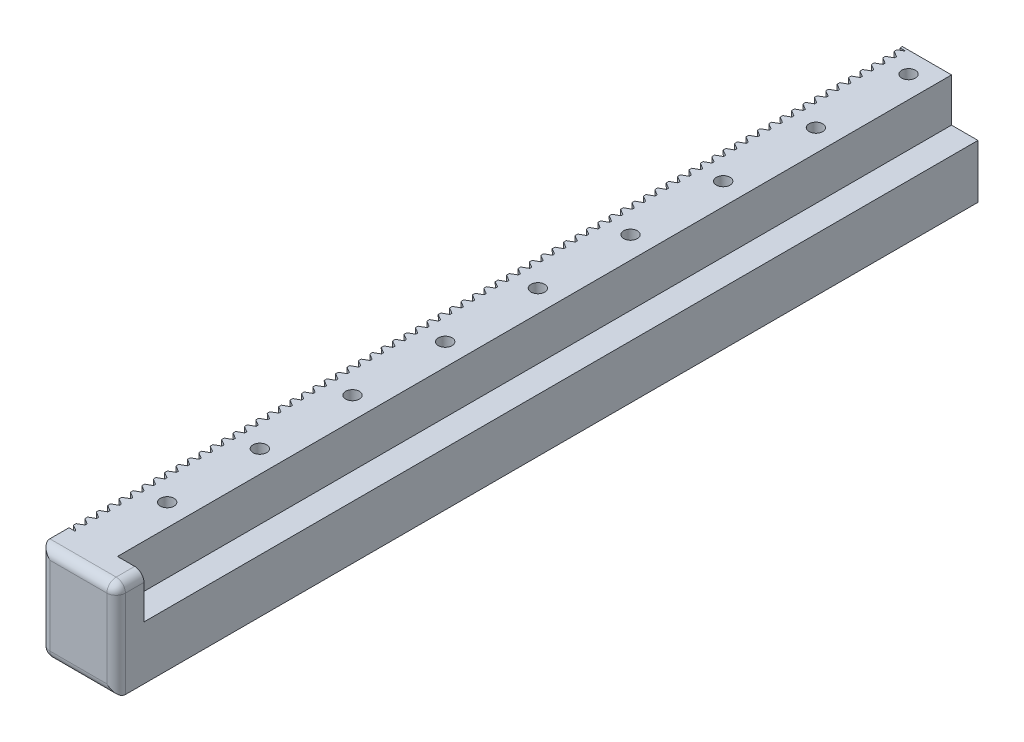
SolidWorks part; units mm, degrees
ref_plane "Front Plane" through (0, 0, 0) normal (0, 0, 1) x (1, 0, 0)
ref_plane "Top Plane" through (0, 0, 0) normal (0, 1, 0) x (1, 0, 0)
ref_plane "Right Plane" through (0, 0, 0) normal (1, 0, 0) x (0, 0, -1)
sketch "Sketch1" plane through (0, 0, 0) normal (0, 0, 1) x (1, 0, 0)
  line L0 (8.155, 3.5595) -> (8.155, -2.2289)
  line L1 (6.255, 0) -> (0.2882, 0)
  line L3 (0, 8.253) -> (5.3, 8.253)
  line L4 (5.3, 3.5595) -> (5.3, 8.253)
  line L5 (0.2882, 0) -> (0, 8.253)
  line L7 (5.3, 3.5595) -> (8.155, 3.5595)
  line L11 (8.155, -2.2289) -> (6.255, -2.2289)
  line L12 (6.255, 0) -> (6.255, -2.2289)
  dimension "D1" = 5.3
  dimension "D2" = 8.253
  dimension "D3" = 1.9
  dimension "D4" = 2.855
  dimension "D6" = 88
extrude "Boss-Extrude1" add sketch "Sketch1" along normal blind 90
sketch "Sketch2" plane through (0, 0, 90) normal (0, 0, 1) x (1, 0, 0)
  line L1 (0, 8.253) -> (8.155, 8.253)
  line L2 (0, 8.253) -> (0, -2.2289)
  line L3 (0, -2.2289) -> (8.155, -2.2289)
  line L4 (8.155, 8.253) -> (8.155, -2.2289)
extrude "Boss-Extrude2" add sketch "Sketch2" along normal blind 3
fillet "Fillet1" radius 1 6 edges at (4.0775, 8.253, 93) (8.155, 3.0121, 93) (4.0775, -2.2289, 93) (0, 3.0121, 93) (0, -2.2289, 91.5) (8.155, 8.253, 91.5)
sketch "Sketch3" plane through (5.3, 0, 0) normal (0, 1, 0) x (0, 0, -1)
  line L0 (-87.5812, 4.6774) -> (-88.0715, 5.5507)
  line L1 (-88.0715, 5.5507) -> (-88.5898, 4.6774)
  line L2 (-88.8112, 4.6774) -> (-89.3015, 5.5507)
  line L3 (-89.3015, 5.5507) -> (-89.8198, 4.6774)
  line L4 (-89.3983, 4.4813) -> (-88.7803, 4.4739) [skipped]
  line L5 (-86.3512, 4.6774) -> (-86.8415, 5.5507)
  line L6 (-86.8415, 5.5507) -> (-87.3598, 4.6774)
  line L7 (-85.1212, 4.6774) -> (-85.6115, 5.5507)
  line L8 (-85.6115, 5.5507) -> (-86.1298, 4.6774)
  line L149 (-89.9324, 4.6774) -> (-89.9324, 6.9221)
  line L150 (-89.9324, 6.9221) -> (-85.1212, 6.9221)
  line L154 (-89.8198, 4.6774) -> (-89.9324, 4.6774)
  line L155 (-88.5898, 4.6774) -> (-88.8112, 4.6774)
  line L156 (-87.3598, 4.6774) -> (-87.5812, 4.6774)
  line L157 (-86.1298, 4.6774) -> (-86.3512, 4.6774)
  line L158 (-85.1212, 6.9221) -> (-85.1212, 4.6774)
  line L160 (-83.1621, 7.6054) -> (-83.4775, 7.0739) [skipped]
  line L161 (-83.735, 6.5902) -> (-84.3402, 7.668) [skipped]
  line L162 (-81.9321, 7.6054) -> (-82.5629, 6.5424) [skipped]
  line L163 (-82.505, 6.5902) -> (-83.1102, 7.668) [skipped]
  line L164 (-80.7021, 7.6054) -> (-81.3329, 6.5424) [skipped]
  line L165 (-81.275, 6.5902) -> (-81.8802, 7.668) [skipped]
  line L166 (-79.4721, 7.6054) -> (-80.1029, 6.5424) [skipped]
  line L167 (-80.045, 6.5902) -> (-80.6502, 7.668) [skipped]
  line L168 (-78.2421, 7.6054) -> (-78.8729, 6.5424) [skipped]
  line L169 (-78.815, 6.5902) -> (-79.4202, 7.668) [skipped]
  line L170 (-77.0121, 7.6054) -> (-77.6429, 6.5424) [skipped]
  line L171 (-75.7821, 7.6054) -> (-76.4129, 6.5424) [skipped]
  line L172 (-84.965, 6.5902) -> (-85.5702, 7.668) [skipped]
  line L173 (-49.295, 6.5902) -> (-49.9002, 7.668) [skipped]
  line L174 (-47.4921, 7.6054) -> (-48.1229, 6.5424) [skipped]
  line L175 (-48.065, 6.5902) -> (-48.6702, 7.668) [skipped]
  line L176 (-46.2621, 7.6054) -> (-46.8929, 6.5424) [skipped]
  line L177 (-46.835, 6.5902) -> (-47.4402, 7.668) [skipped]
  line L178 (-45.0321, 7.6054) -> (-45.6629, 6.5424) [skipped]
  line L179 (-45.605, 6.5902) -> (-46.2102, 7.668) [skipped]
  line L180 (-43.8021, 7.6054) -> (-44.4329, 6.5424) [skipped]
  line L181 (-44.375, 6.5902) -> (-44.9802, 7.668) [skipped]
  line L182 (-42.5721, 7.6054) -> (-43.2029, 6.5424) [skipped]
  line L183 (-43.145, 6.5902) -> (-43.7502, 7.668) [skipped]
  line L184 (-41.3421, 7.6054) -> (-41.9729, 6.5424) [skipped]
  line L185 (-41.915, 6.5902) -> (-42.5202, 7.668) [skipped]
  line L186 (-40.1121, 7.6054) -> (-40.7429, 6.5424) [skipped]
  line L187 (-40.685, 6.5902) -> (-41.2902, 7.668) [skipped]
  line L188 (-38.8821, 7.6054) -> (-39.5129, 6.5424) [skipped]
  line L189 (-37.6521, 7.6054) -> (-38.2829, 6.5424) [skipped]
  line L190 (-38.225, 6.5902) -> (-38.8302, 7.668) [skipped]
  line L191 (-36.4221, 7.6054) -> (-37.0529, 6.5424) [skipped]
  line L192 (-36.995, 6.5902) -> (-37.6002, 7.668) [skipped]
  line L193 (-35.1921, 7.6054) -> (-35.8229, 6.5424) [skipped]
  line L194 (-35.765, 6.5902) -> (-36.3702, 7.668) [skipped]
  line L195 (-33.9621, 7.6054) -> (-34.5929, 6.5424) [skipped]
  line L196 (-34.535, 6.5902) -> (-35.1402, 7.668) [skipped]
  line L197 (-32.7321, 7.6054) -> (-33.3629, 6.5424) [skipped]
  line L198 (-33.305, 6.5902) -> (-33.9102, 7.668) [skipped]
  line L199 (-31.5021, 7.6054) -> (-32.1329, 6.5424) [skipped]
  line L200 (-32.075, 6.5902) -> (-32.6802, 7.668) [skipped]
  line L201 (-30.2721, 7.6054) -> (-30.9029, 6.5424) [skipped]
  line L202 (-30.845, 6.5902) -> (-31.4502, 7.668) [skipped]
  line L203 (-29.0421, 7.6054) -> (-29.6729, 6.5424) [skipped]
  line L204 (-29.615, 6.5902) -> (-30.2202, 7.668) [skipped]
  line L205 (-27.8121, 7.6054) -> (-28.4429, 6.5424) [skipped]
  line L206 (-28.385, 6.5902) -> (-28.9902, 7.668) [skipped]
  line L207 (-26.5821, 7.6054) -> (-27.2129, 6.5424) [skipped]
  line L208 (-27.155, 6.5902) -> (-27.7602, 7.668) [skipped]
  line L209 (-25.3521, 7.6054) -> (-25.9829, 6.5424) [skipped]
  line L210 (-25.925, 6.5902) -> (-26.5302, 7.668) [skipped]
  line L211 (-24.1221, 7.6054) -> (-24.7529, 6.5424) [skipped]
  line L212 (-24.695, 6.5902) -> (-25.3002, 7.668) [skipped]
  line L213 (-22.8921, 7.6054) -> (-23.5229, 6.5424) [skipped]
  line L214 (-23.465, 6.5902) -> (-24.0702, 7.668) [skipped]
  line L215 (-21.6621, 7.6054) -> (-22.2929, 6.5424) [skipped]
  line L216 (-22.235, 6.5902) -> (-22.8402, 7.668) [skipped]
  line L217 (-20.4321, 7.6054) -> (-21.0629, 6.5424) [skipped]
  line L218 (-21.005, 6.5902) -> (-21.6102, 7.668) [skipped]
  line L219 (-19.2021, 7.6054) -> (-19.8329, 6.5424) [skipped]
  line L220 (-19.775, 6.5902) -> (-20.3802, 7.668) [skipped]
  line L221 (-17.9721, 7.6054) -> (-18.6029, 6.5424) [skipped]
  line L222 (-18.545, 6.5902) -> (-19.1502, 7.668) [skipped]
  line L223 (-16.7421, 7.6054) -> (-17.3729, 6.5424) [skipped]
  line L224 (-17.315, 6.5902) -> (-17.9202, 7.668) [skipped]
  line L225 (-15.5121, 7.6054) -> (-16.1429, 6.5424) [skipped]
  line L226 (-16.085, 6.5902) -> (-16.6902, 7.668) [skipped]
  line L227 (-14.2821, 7.6054) -> (-14.9129, 6.5424) [skipped]
  line L228 (-14.855, 6.5902) -> (-15.4602, 7.668) [skipped]
  line L229 (-13.0521, 7.6054) -> (-13.6829, 6.5424) [skipped]
  line L230 (-13.625, 6.5902) -> (-14.2302, 7.668) [skipped]
  line L231 (-11.8221, 7.6054) -> (-12.4529, 6.5424) [skipped]
  line L232 (-12.395, 6.5902) -> (-13.0002, 7.668) [skipped]
  line L233 (-10.5921, 7.6054) -> (-11.2229, 6.5424) [skipped]
  line L234 (-11.165, 6.5902) -> (-11.7702, 7.668) [skipped]
  line L235 (-9.3621, 7.6054) -> (-9.9929, 6.5424) [skipped]
  line L236 (-9.935, 6.5902) -> (-10.5402, 7.668) [skipped]
  line L237 (-8.1321, 7.6054) -> (-8.7629, 6.5424) [skipped]
  line L238 (-8.705, 6.5902) -> (-9.3102, 7.668) [skipped]
  line L239 (-6.9021, 7.6054) -> (-7.5329, 6.5424) [skipped]
  line L240 (-7.475, 6.5902) -> (-8.0802, 7.668) [skipped]
  line L241 (-5.6721, 7.6054) -> (-6.3029, 6.5424) [skipped]
  line L242 (-6.245, 6.5902) -> (-6.8502, 7.668) [skipped]
  line L243 (-4.4421, 7.6054) -> (-5.0729, 6.5424) [skipped]
  line L244 (-5.015, 6.5902) -> (-5.6202, 7.668) [skipped]
  line L245 (-3.2121, 7.6054) -> (-3.8429, 6.5424) [skipped]
  line L246 (-3.785, 6.5902) -> (-4.3902, 7.668) [skipped]
  line L247 (-1.9821, 7.6054) -> (-2.6129, 6.5424) [skipped]
  line L248 (-2.555, 6.5902) -> (-3.1602, 7.668) [skipped]
  line L249 (-0.7521, 7.6054) -> (-1.3829, 6.5424) [skipped]
  line L250 (-1.325, 6.5902) -> (-1.9302, 7.668) [skipped]
  line L251 (0.4779, 7.6054) -> (-0.1529, 6.5424) [skipped]
  line L252 (-0.095, 6.5902) -> (-0.7002, 7.668) [skipped]
  line L253 (1.7079, 7.6054) -> (1.0771, 6.5424) [skipped]
  line L254 (-39.455, 6.5902) -> (-40.0602, 7.668) [skipped]
  line L255 (-76.355, 6.5902) -> (-76.9602, 7.668) [skipped]
  line L256 (-74.5521, 7.6054) -> (-75.1829, 6.5424) [skipped]
  line L257 (-75.125, 6.5902) -> (-75.7302, 7.668) [skipped]
  line L258 (-73.3221, 7.6054) -> (-73.9529, 6.5424) [skipped]
  line L259 (-73.895, 6.5902) -> (-74.5002, 7.668) [skipped]
  line L260 (-72.0921, 7.6054) -> (-72.7229, 6.5424) [skipped]
  line L261 (-72.665, 6.5902) -> (-73.2702, 7.668) [skipped]
  line L262 (-70.8621, 7.6054) -> (-71.4929, 6.5424) [skipped]
  line L263 (-71.435, 6.5902) -> (-72.0402, 7.668) [skipped]
  line L264 (-69.6321, 7.6054) -> (-70.2629, 6.5424) [skipped]
  line L265 (-70.205, 6.5902) -> (-70.8102, 7.668) [skipped]
  line L266 (-68.4021, 7.6054) -> (-69.0329, 6.5424) [skipped]
  line L267 (-68.975, 6.5902) -> (-69.5802, 7.668) [skipped]
  line L268 (-67.1721, 7.6054) -> (-67.8029, 6.5424) [skipped]
  line L269 (-67.745, 6.5902) -> (-68.3502, 7.668) [skipped]
  line L270 (-65.9421, 7.6054) -> (-66.5729, 6.5424) [skipped]
  line L271 (-66.515, 6.5902) -> (-67.1202, 7.668) [skipped]
  line L272 (-64.7121, 7.6054) -> (-65.3429, 6.5424) [skipped]
  line L273 (-65.285, 6.5902) -> (-65.8902, 7.668) [skipped]
  line L274 (-63.4821, 7.6054) -> (-64.1129, 6.5424) [skipped]
  line L275 (-64.055, 6.5902) -> (-64.6602, 7.668) [skipped]
  line L276 (-62.2521, 7.6054) -> (-62.8829, 6.5424) [skipped]
  line L277 (-62.825, 6.5902) -> (-63.4302, 7.668) [skipped]
  line L278 (-61.0221, 7.6054) -> (-61.6529, 6.5424) [skipped]
  line L279 (-61.595, 6.5902) -> (-62.2002, 7.668) [skipped]
  line L280 (-59.7921, 7.6054) -> (-60.4229, 6.5424) [skipped]
  line L281 (-60.365, 6.5902) -> (-60.9702, 7.668) [skipped]
  line L282 (-58.5621, 7.6054) -> (-59.1929, 6.5424) [skipped]
  line L283 (-59.135, 6.5902) -> (-59.7402, 7.668) [skipped]
  line L284 (-57.3321, 7.6054) -> (-57.9629, 6.5424) [skipped]
  line L285 (-57.905, 6.5902) -> (-58.5102, 7.668) [skipped]
  line L286 (-56.1021, 7.6054) -> (-56.7329, 6.5424) [skipped]
  line L287 (-56.675, 6.5902) -> (-57.2802, 7.668) [skipped]
  line L288 (-54.8721, 7.6054) -> (-55.5029, 6.5424) [skipped]
  line L289 (-55.445, 6.5902) -> (-56.0502, 7.668) [skipped]
  line L290 (-53.6421, 7.6054) -> (-54.2729, 6.5424) [skipped]
  line L291 (-54.215, 6.5902) -> (-54.8202, 7.668) [skipped]
  line L292 (-52.4121, 7.6054) -> (-53.0429, 6.5424) [skipped]
  line L293 (-52.985, 6.5902) -> (-53.5902, 7.668) [skipped]
  line L294 (-51.1821, 7.6054) -> (-51.8129, 6.5424) [skipped]
  line L295 (-51.755, 6.5902) -> (-52.3602, 7.668) [skipped]
  line L296 (-49.9521, 7.6054) -> (-50.5829, 6.5424) [skipped]
  line L297 (-50.525, 6.5902) -> (-51.1302, 7.668) [skipped]
  line L298 (-48.7221, 7.6054) -> (-49.3529, 6.5424) [skipped]
  line L299 (-77.585, 6.5902) -> (-78.1902, 7.668) [skipped]
  circle A0 centre (-89.3101, 4.8371) radius 0.3568 construction
  arc A1 (-87.7689, 5.0118) -> (-88.3869, 5.0193) centre (-88.0801, 4.8371) ccw construction
  arc A2 (-86.5389, 5.0118) -> (-87.1692, 4.6774) centre (-86.8501, 4.8371) ccw construction
  arc A3 (-85.9392, 4.6774) -> (-85.301, 4.6774) centre (-85.6201, 4.8371) ccw construction
  arc A74 (-85.3089, 5.0118) -> (-85.9269, 5.0193) centre (-85.6201, 4.8371) ccw construction
  arc A75 (-84.7112, 4.6816) -> (-84.7116, 4.6824) centre (-84.3901, 4.8371) ccw construction
  circle A76 centre (-83.1601, 4.8371) radius 0.3568 construction
  circle A77 centre (-81.9301, 4.8371) radius 0.3568 construction
  circle A78 centre (-80.7001, 4.8371) radius 0.3568 construction
  circle A79 centre (-79.4701, 4.8371) radius 0.3568 construction
  circle A80 centre (-78.2401, 4.8371) radius 0.3568 construction
  circle A81 centre (-77.0101, 4.8371) radius 0.3568 construction
  circle A82 centre (-48.7201, 4.8371) radius 0.3568 construction
  circle A83 centre (-47.4901, 4.8371) radius 0.3568 construction
  circle A84 centre (-46.2601, 4.8371) radius 0.3568 construction
  circle A85 centre (-45.0301, 4.8371) radius 0.3568 construction
  circle A86 centre (-43.8001, 4.8371) radius 0.3568 construction
  circle A87 centre (-42.5701, 4.8371) radius 0.3568 construction
  circle A88 centre (-41.3401, 4.8371) radius 0.3568 construction
  circle A89 centre (-40.1101, 4.8371) radius 0.3568 construction
  circle A90 centre (-38.8801, 4.8371) radius 0.3568 construction
  circle A91 centre (-37.6501, 4.8371) radius 0.3568 construction
  circle A92 centre (-36.4201, 4.8371) radius 0.3568 construction
  circle A93 centre (-35.1901, 4.8371) radius 0.3568 construction
  circle A94 centre (-33.9601, 4.8371) radius 0.3568 construction
  circle A95 centre (-32.7301, 4.8371) radius 0.3568 construction
  circle A96 centre (-31.5001, 4.8371) radius 0.3568 construction
  circle A97 centre (-30.2701, 4.8371) radius 0.3568 construction
  circle A98 centre (-29.0401, 4.8371) radius 0.3568 construction
  circle A99 centre (-27.8101, 4.8371) radius 0.3568 construction
  circle A100 centre (-26.5801, 4.8371) radius 0.3568 construction
  circle A101 centre (-25.3501, 4.8371) radius 0.3568 construction
  circle A102 centre (-24.1201, 4.8371) radius 0.3568 construction
  circle A103 centre (-22.8901, 4.8371) radius 0.3568 construction
  circle A104 centre (-21.6601, 4.8371) radius 0.3568 construction
  circle A105 centre (-20.4301, 4.8371) radius 0.3568 construction
  circle A106 centre (-19.2001, 4.8371) radius 0.3568 construction
  circle A107 centre (-17.9701, 4.8371) radius 0.3568 construction
  circle A108 centre (-16.7401, 4.8371) radius 0.3568 construction
  circle A109 centre (-15.5101, 4.8371) radius 0.3568 construction
  circle A110 centre (-14.2801, 4.8371) radius 0.3568 construction
  circle A111 centre (-13.0501, 4.8371) radius 0.3568 construction
  circle A112 centre (-11.8201, 4.8371) radius 0.3568 construction
  circle A113 centre (-10.5901, 4.8371) radius 0.3568 construction
  circle A114 centre (-9.3601, 4.8371) radius 0.3568 construction
  circle A115 centre (-8.1301, 4.8371) radius 0.3568 construction
  circle A116 centre (-6.9001, 4.8371) radius 0.3568 construction
  circle A117 centre (-5.6701, 4.8371) radius 0.3568 construction
  circle A118 centre (-4.4401, 4.8371) radius 0.3568 construction
  circle A119 centre (-3.2101, 4.8371) radius 0.3568 construction
  circle A120 centre (-1.9801, 4.8371) radius 0.3568 construction
  circle A121 centre (-0.7501, 4.8371) radius 0.3568 construction
  circle A122 centre (0.4799, 4.8371) radius 0.3568 construction
  circle A123 centre (-75.7801, 4.8371) radius 0.3568 construction
  circle A124 centre (-74.5501, 4.8371) radius 0.3568 construction
  circle A125 centre (-73.3201, 4.8371) radius 0.3568 construction
  circle A126 centre (-72.0901, 4.8371) radius 0.3568 construction
  circle A127 centre (-70.8601, 4.8371) radius 0.3568 construction
  circle A128 centre (-69.6301, 4.8371) radius 0.3568 construction
  circle A129 centre (-68.4001, 4.8371) radius 0.3568 construction
  circle A130 centre (-67.1701, 4.8371) radius 0.3568 construction
  circle A131 centre (-65.9401, 4.8371) radius 0.3568 construction
  circle A132 centre (-64.7101, 4.8371) radius 0.3568 construction
  circle A133 centre (-63.4801, 4.8371) radius 0.3568 construction
  circle A134 centre (-62.2501, 4.8371) radius 0.3568 construction
  circle A135 centre (-61.0201, 4.8371) radius 0.3568 construction
  circle A136 centre (-59.7901, 4.8371) radius 0.3568 construction
  circle A137 centre (-58.5601, 4.8371) radius 0.3568 construction
  circle A138 centre (-57.3301, 4.8371) radius 0.3568 construction
  circle A139 centre (-56.1001, 4.8371) radius 0.3568 construction
  circle A140 centre (-54.8701, 4.8371) radius 0.3568 construction
  circle A141 centre (-53.6401, 4.8371) radius 0.3568 construction
  circle A142 centre (-52.4101, 4.8371) radius 0.3568 construction
  circle A143 centre (-51.1801, 4.8371) radius 0.3568 construction
  circle A144 centre (-49.9501, 4.8371) radius 0.3568 construction
  dimension "D2" = 74
extrude "Cut-Extrude2" cut sketch "Sketch3" along normal blind 13
pattern_linear "LPattern1" count 24 spacing 3.69 along (0, 0, -1) of "Cut-Extrude2"
sketch "Sketch4" plane through (0, 8.253, 0) normal (0, 1, 0) x (1, 0, 0)
  circle A0 centre (2.9148, -2.2514) radius 0.7382
  circle A1 centre (2.9148, -12.2514) radius 0.7382
  circle A2 centre (2.9148, -22.2514) radius 0.7382
  circle A3 centre (2.9148, -32.2514) radius 0.7382
  circle A4 centre (2.9148, -42.2514) radius 0.7382
  circle A5 centre (2.9148, -52.2514) radius 0.7382
  circle A6 centre (2.9148, -62.2514) radius 0.7382
  circle A7 centre (2.9148, -72.2514) radius 0.7382
  circle A8 centre (2.9148, -82.2514) radius 0.7382
  dimension "D1" = 9
extrude "Cut-Extrude3" cut sketch "Sketch4" against normal blind 18
